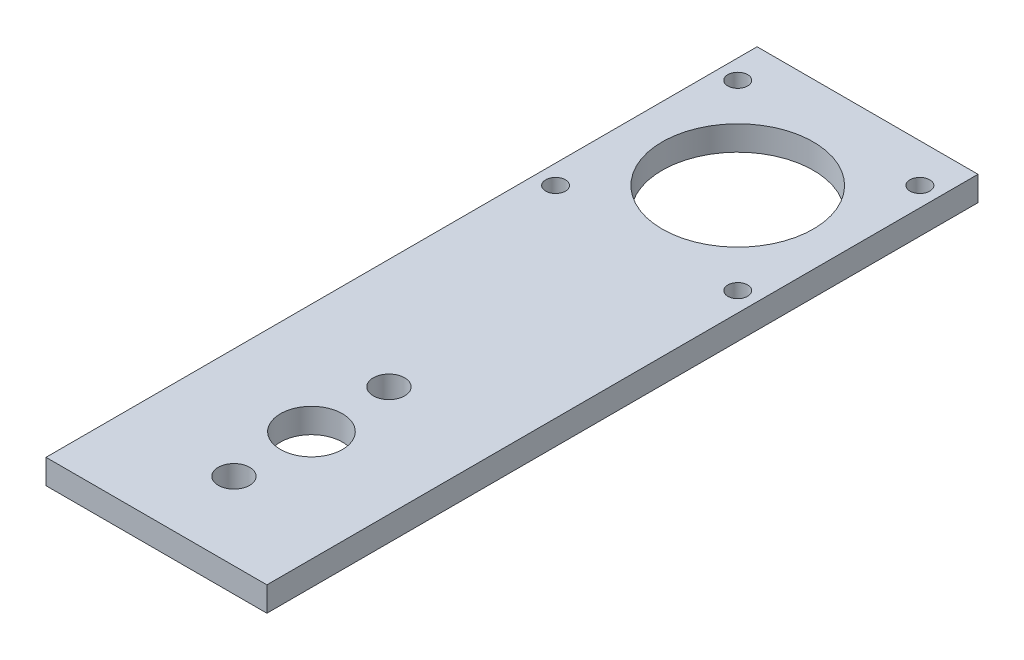
SolidWorks part; units mm, degrees
ref_plane "Top Plane" through (0, 0, 0) normal (0, 0, 1) x (1, 0, 0)
ref_plane "Front Plane" through (0, 0, 0) normal (0, 1, 0) x (1, 0, 0)
ref_plane "Right Plane" through (0, 0, 0) normal (1, 0, 0) x (0, 0, -1)
sketch "Sketch1" plane through (0, 0, 0) normal (0, 1, 0) x (1, 0, 0)
  line L0 (0, 0) -> (0, -150) construction
  line L1 (-28.5, 33.5) -> (28.5, 33.5)
  line L2 (-28.5, 33.5) -> (-28.5, -150)
  line L3 (-28.5, -150) -> (28.5, -150)
  line L4 (28.5, 33.5) -> (28.5, -150)
  line L5 (-23.5, -23.5) -> (23.5, -23.5) construction
  line L6 (-23.5, -23.5) -> (-23.5, 23.5) construction
  line L7 (-23.5, 23.5) -> (23.5, 23.5) construction
  line L8 (23.5, -23.5) -> (23.5, 23.5) construction
  line L9 (-23.5, -23.5) -> (23.5, 23.5) construction
  line L10 (-23.5, 23.5) -> (23.5, -23.5) construction
  circle A0 centre (0, 0) radius 19.5
  circle A1 centre (-23.5, 23.5) radius 2.55
  circle A2 centre (23.5, 23.5) radius 2.55
  circle A3 centre (23.5, -23.5) radius 2.55
  circle A4 centre (-23.5, -23.5) radius 2.55
  circle A5 centre (0, -90) radius 4.05
  circle A6 centre (0, -130) radius 4.05
  circle A7 centre (0, -110) radius 8
  dimension "D3" = 47
  dimension "D5" = 39
  dimension "D6" = 5.1
  dimension "D7" = 90
  dimension "D9" = 8.1
  dimension "D10" = 16
  dimension "D1" = 57
  dimension "D2" = 20
  dimension "D4" = 10
  dimension "D8" = 40
  dimension "D11" = 20
extrude "Boss-Extrude1" add sketch "Sketch1" along normal blind 6.35
